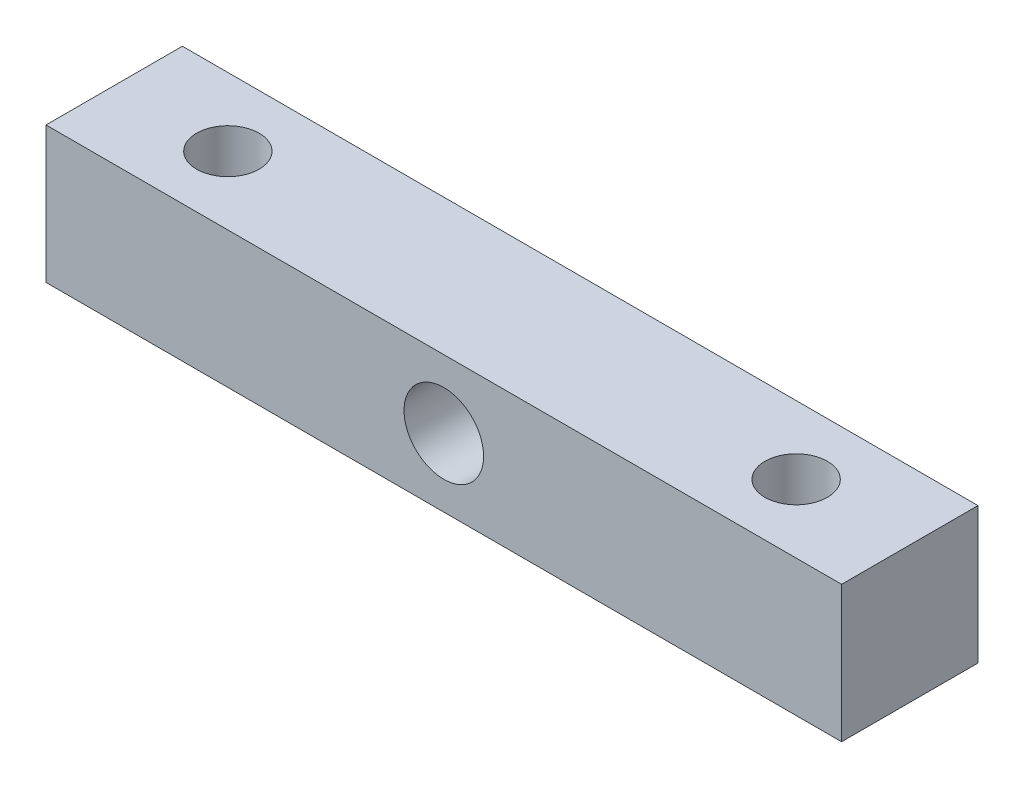
SolidWorks part; units mm, degrees
ref_plane "Front Plane" through (0, 0, 0) normal (0, 0, 1) x (1, 0, 0)
ref_plane "Top Plane" through (0, 0, 0) normal (0, 1, 0) x (1, 0, 0)
ref_plane "Right Plane" through (0, 0, 0) normal (1, 0, 0) x (0, 0, -1)
sketch "Sketch1" plane through (0, 0, 0) normal (0, 1, 0) x (1, 0, 0)
  line L0 (0, 0) -> (0, 12)
  line L1 (0, 0) -> (70, 0)
  line L2 (0, 12) -> (70, 12)
  line L3 (70, 0) -> (70, 12)
  dimension "D1" = 70
  dimension "D2" = 12
extrude "Boss-Extrude1" add sketch "Sketch1" along normal blind 12
hole_wizard "M8x1.0 Tapped Hole1" positions "Sketch4" profile "Sketch3" tap size "M8x1.0" standard "Ansi Metric" end condition through all
sketch "Sketch4" plane through (0, 0, 0) normal (0, 0, 1) x (1, 0, 0)
  line L0 (0, 12) -> (70, 12) construction
  line L1 (0, 12) -> (0, 0) construction
  point P0 (35, 6)
  dimension "D1" = 6
  dimension "D2" = 35
sketch "Sketch3" plane through (35, 6, 0) normal (1, 0, 0) x (0, -1, 0)
  line L0 (0, 0) -> (0, 12)
  line L1 (0, 12) -> (3.5, 12)
  line L2 (3.5, 12) -> (3.5, 0)
  line L5 (3.5, 0) -> (0, 0)
  line L11 (0, -6.35) -> (0, 107.95) construction
  dimension "Thru Tap Drill Dia." = 7
  dimension "Thru Tap Drill Depth" = 12
cosmetic thread "Hole Thread1" parameters "D2"=8
hole_wizard "Ø5.5 (5.5) Diameter Hole1" positions "Sketch6" profile "Sketch7" hole size "Ø5.5" standard "Ansi Metric" end condition through all
sketch "Sketch6" plane through (0, 12, 0) normal (0, 1, 0) x (-1, 0, 0)
  line L0 (-70, -12) -> (0, -12) construction
  line L1 (0, -12) -> (0, 0) construction
  line L2 (-70, 0) -> (-70, -12) construction
  point P0 (-10, -6)
  point P1 (-60, -6)
  dimension "D1" = 6
  dimension "D2" = 10
  dimension "D3" = 10
sketch "Sketch7" plane through (10, 12, -6) normal (1, 0, 0) x (0, 0, 1)
  line L0 (0, 0) -> (0, 12)
  line L1 (0, 12) -> (2.75, 12)
  line L2 (2.75, 12) -> (2.75, 0)
  line L5 (2.75, 0) -> (0, 0)
  line L11 (0, -6.35) -> (0, 107.95) construction
  dimension "Thru Hole Dia." = 5.5
  dimension "Thru Hole Depth" = 12
